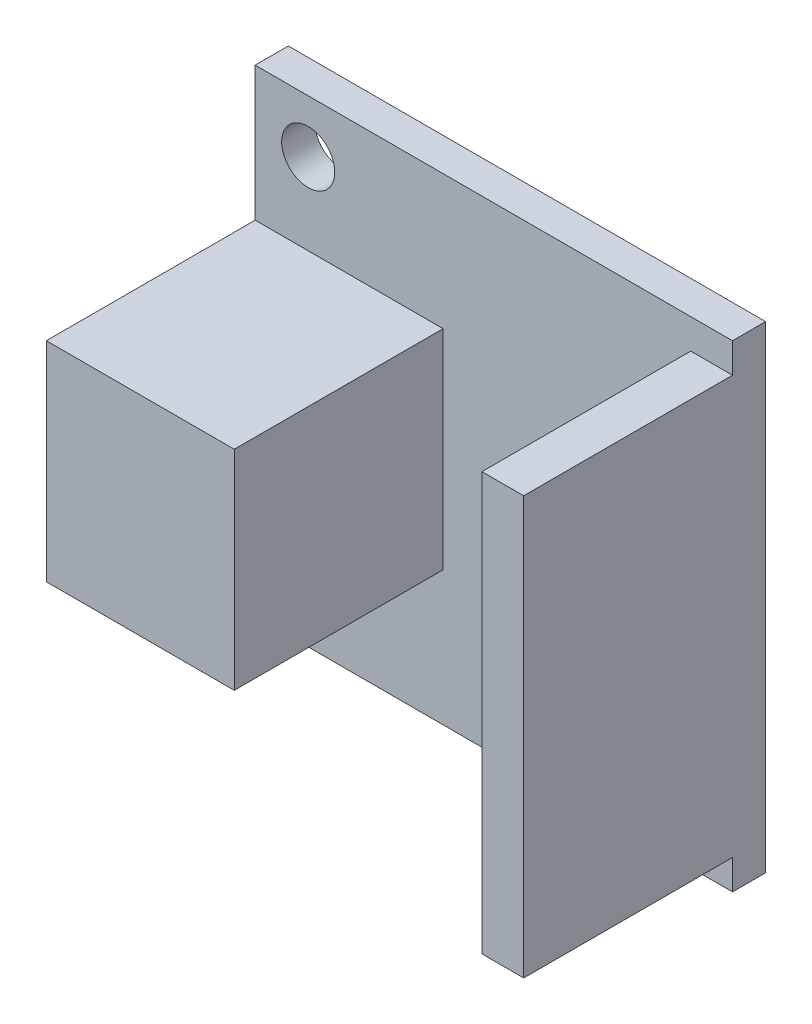
SolidWorks part; units mm, degrees
ref_plane "Front Plane" through (0, 0, 0) normal (0, 0, 1) x (1, 0, 0)
ref_plane "Top Plane" through (0, 0, 0) normal (0, 1, 0) x (1, 0, 0)
ref_plane "Right Plane" through (0, 0, 0) normal (1, 0, 0) x (0, 0, -1)
sketch "Sketch1" plane through (0, 0, 0) normal (0, 0, 1) x (1, 0, 0)
  line L1 (-11.43, 11.43) -> (11.43, 11.43)
  line L2 (-11.43, 11.43) -> (-11.43, -11.43)
  line L3 (-11.43, -11.43) -> (11.43, -11.43)
  line L4 (11.43, 11.43) -> (11.43, -11.43)
  line L5 (-11.43, 11.43) -> (11.43, -11.43) construction
  line L6 (-11.43, -11.43) -> (11.43, 11.43) construction
  point P0 (0, 0)
  dimension "D1" = 22.86
  dimension "D2" = 22.86
extrude "Boss-Extrude1" add sketch "Sketch1" along normal blind 1.5875
sketch "Sketch2" plane through (0, 0, 1.5875) normal (0, 0, 1) x (1, 0, 0)
  line L0 (-11.43, 11.43) -> (-11.43, -11.43) construction
  line L1 (-11.43, 5) -> (-2.43, 5)
  line L2 (-11.43, 5) -> (-11.43, -5)
  line L3 (-11.43, -5) -> (-2.43, -5)
  line L4 (-2.43, 5) -> (-2.43, -5)
  line L5 (-11.43, 5) -> (-2.43, -5) construction
  line L6 (-11.43, -5) -> (-2.43, 5) construction
  point P0 (-6.93, 0)
  point P5 (-4.3109, 0)
  point P7 (-11.43, 5)
  dimension "D1" = 10
  dimension "D2" = 9
extrude "Boss-Extrude2" add sketch "Sketch2" along normal blind 10
sketch "Sketch4" plane through (0, 0, 1.5875) normal (0, 0, 1) x (1, 0, 0)
  line L0 (11.43, -11.43) -> (11.43, 11.43) construction
  line L1 (9.43, 10) -> (11.43, 10)
  line L2 (9.43, 10) -> (9.43, -10)
  line L3 (9.43, -10) -> (11.43, -10)
  line L4 (11.43, 10) -> (11.43, -10)
  line L5 (9.43, 10) -> (11.43, -10) construction
  line L6 (9.43, -10) -> (11.43, 10) construction
  point P0 (10.43, 0)
  point P7 (0, 0)
  dimension "D1" = 20
  dimension "D2" = 2
extrude "Boss-Extrude3" add sketch "Sketch4" along normal blind 10
sketch "Sketch5" plane through (0, 0, 1.5875) normal (0, 0, 1) x (1, 0, 0)
  line L1 (8.89, -8.89) -> (-8.89, -8.89)
  line L2 (8.89, -8.89) -> (8.89, 8.89)
  line L3 (8.89, 8.89) -> (-8.89, 8.89)
  line L4 (-8.89, -8.89) -> (-8.89, 8.89)
  line L5 (8.89, -8.89) -> (-8.89, 8.89) construction
  line L6 (8.89, 8.89) -> (-8.89, -8.89) construction
  point P0 (0, 0)
  dimension "D1" = 8.89
  dimension "D2" = 17.78
sketch "Sketch6" plane through (0, 0, 1.5875) normal (0, 0, 1) x (1, 0, 0)
  circle A0 centre (-8.89, 8.89) radius 1.27
  circle A1 centre (-8.89, -8.89) radius 1.27
  dimension "D1" = 2.54
  dimension "D2" = 2.54
extrude "Cut-Extrude1" cut sketch "Sketch6" against normal through all
